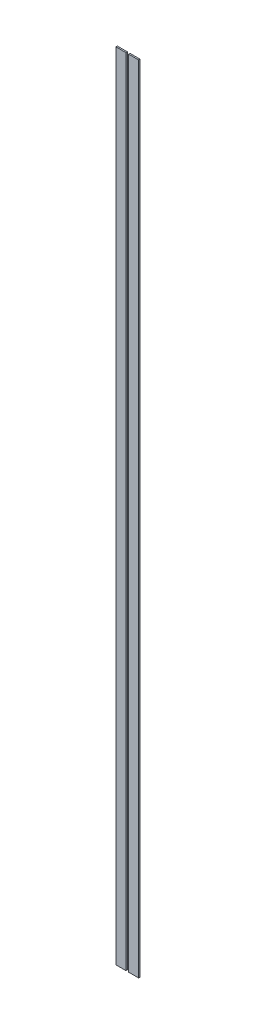
SolidWorks part; units mm, degrees
ref_plane "Plan de face" through (0, 0, 0) normal (0, 0, 1) x (1, 0, 0)
ref_plane "Plan de dessus" through (0, 0, 0) normal (0, 1, 0) x (1, 0, 0)
ref_plane "Plan de droite" through (0, 0, 0) normal (1, 0, 0) x (0, 0, -1)
sketch "Esquisse1" plane through (0, 0, 0) normal (0, 0, 1) x (1, 0, 0)
  line L0 (0, 0) -> (0, 96.3982) construction
  line L1 (8, 280) -> (8, -280)
  line L2 (-8, 280) -> (-1, 280)
  line L3 (-8, 280) -> (-8, -280)
  line L4 (-8, -280) -> (-1, -280)
  line L5 (-1, 280) -> (-1, -280)
  line L6 (8, 280) -> (1, 280)
  line L7 (1, 280) -> (1, -280)
  line L8 (8, -280) -> (1, -280)
  dimension "D1" = 560
  dimension "D2" = 280
  dimension "D3" = 7
  dimension "D4" = 2
extrude "Extrusion1" add sketch "Esquisse1" along normal blind 1
